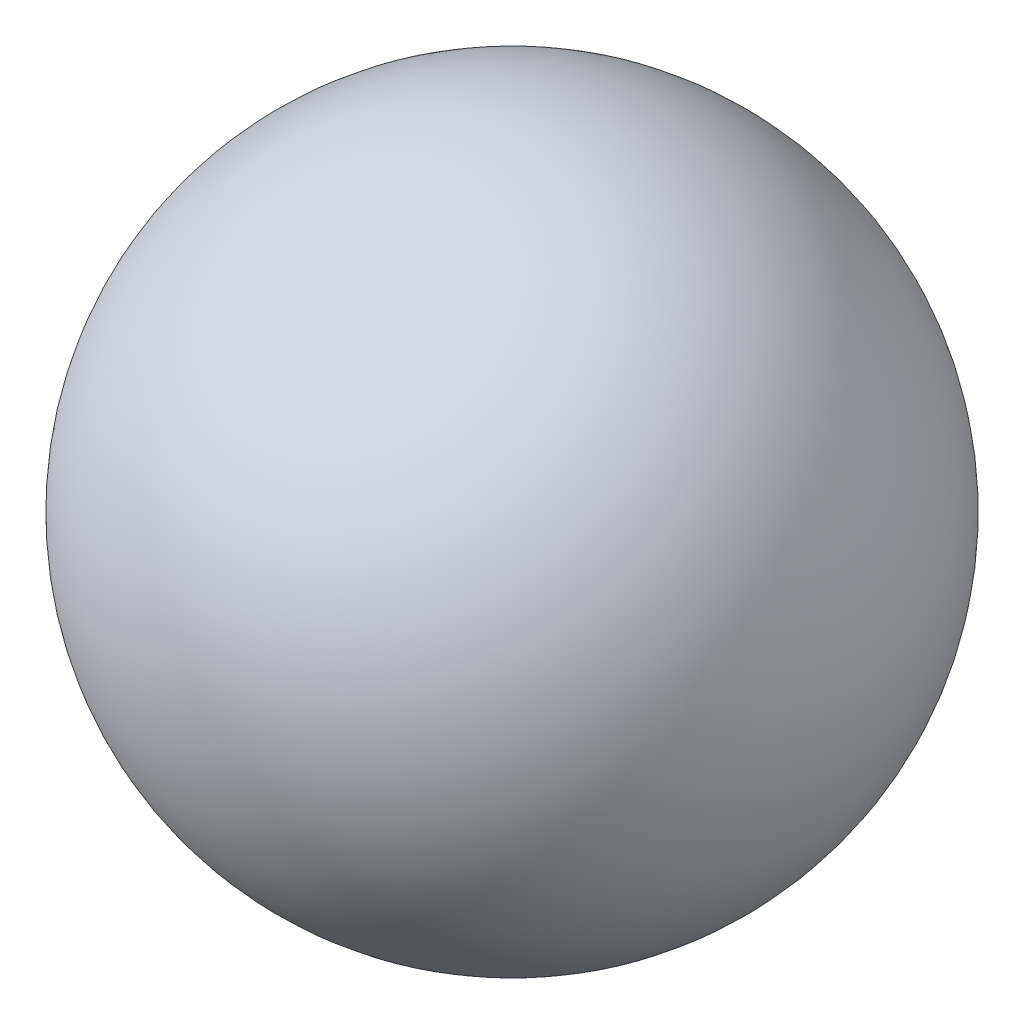
SolidWorks part; units mm, degrees
ref_plane "Front Plane" through (0, 0, 0) normal (0, 0, 1) x (1, 0, 0)
ref_plane "Top Plane" through (0, 0, 0) normal (0, 1, 0) x (1, 0, 0)
ref_plane "Right Plane" through (0, 0, 0) normal (1, 0, 0) x (0, 0, -1)
sketch "Sketch1" plane through (0, 0, 0) normal (0, 0, 1) x (1, 0, 0)
  line L0 (0, 11.5) -> (0, -11.5)
  arc A0 (0, 11.5) -> (0, -11.5) centre (0, 0) cw
  dimension "D1" = 11.5
revolve "Revolve1" add sketch "Sketch1" angle 360 about L0
